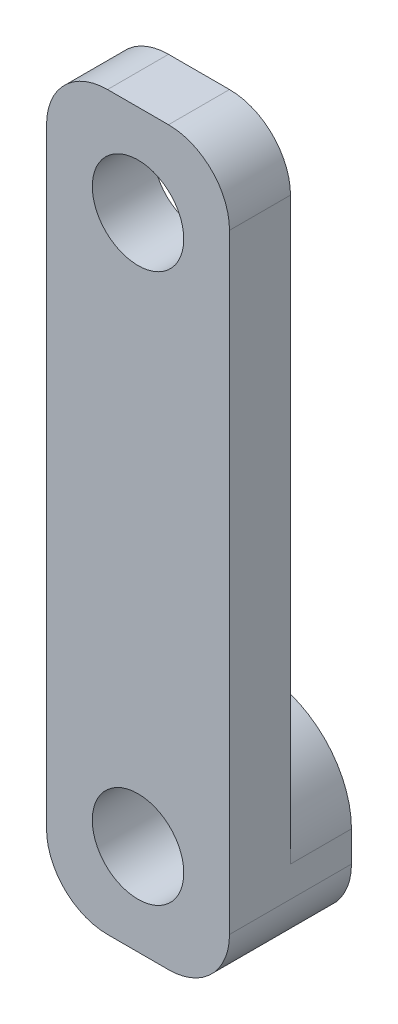
SolidWorks part; units mm, degrees
material "ABS"
ref_plane "Plan de face" through (0, 0, 0) normal (0, 0, 1) x (1, 0, 0)
ref_plane "Plan de dessus" through (0, 0, 0) normal (0, 1, 0) x (1, 0, 0)
ref_plane "Plan de droite" through (0, 0, 0) normal (1, 0, 0) x (0, 0, -1)
sketch "Esquisse2" plane through (0, 0, 0) normal (0, 0, 1) x (1, 0, 0)
  line L0 (0, 0) -> (0, 7.9658) construction
  line L1 (-3, -12) -> (3, -12)
  line L2 (-3, -12) -> (-3, 12)
  line L3 (-3, 12) -> (3, 12)
  line L4 (3, -12) -> (3, 12)
  line L5 (-3, -12) -> (3, 12) construction
  line L6 (-3, 12) -> (3, -12) construction
  circle A0 centre (0, 9) radius 1.5
  circle A1 centre (0, -9) radius 1.5
  point P0 (0, 0)
  dimension "D3" = 3
  dimension "D4" = 0
  dimension "D5" = 3
  dimension "D6" = 3
  dimension "D7" = 3
  dimension "D1" = 18
  dimension "D2" = 6
extrude "Boss.-Extru.2" add sketch "Esquisse2" along normal blind 2
fillet "Congé2" radius 2 4 edges at (-3, 12, 1) (3, 12, 1) (-3, -12, 1) (3, -12, 1)
sketch "Esquisse3" plane through (0, 0, 0) normal (0, 0, -1) x (-1, 0, 0)
  line L4 (-1, -12) -> (1, -12)
  line L5 (3, -10) -> (3, 10)
  line L6 (1, 12) -> (-1, 12)
  line L7 (-3, 10) -> (-3, -10)
  line L8 (-1, -12) -> (1, -12)
  line L9 (3, -10) -> (3, 10)
  line L10 (1, 12) -> (-1, 12)
  line L11 (-3, 10) -> (-3, -10)
  circle A0 centre (0, -9) radius 3
  circle A1 centre (0, -9) radius 1.5
  arc A7 (1, -12) -> (3, -10) centre (1, -10) ccw
  arc A8 (3, 10) -> (1, 12) centre (1, 10) ccw
  arc A9 (-1, 12) -> (-3, 10) centre (-1, 10) ccw
  arc A10 (-3, -10) -> (-1, -12) centre (-1, -10) ccw
  arc A11 (1, -12) -> (3, -10) centre (1, -10) ccw
  arc A12 (3, 10) -> (1, 12) centre (1, 10) ccw
  arc A13 (-1, 12) -> (-3, 10) centre (-1, 10) ccw
  arc A14 (-3, -10) -> (-1, -12) centre (-1, -10) ccw
  line M12 (-1, -12) -> (1, -12)
  arc M13 (1, -12) -> (3, -10) centre (1, -10) ccw
  line M14 (3, -10) -> (3, 10)
  arc M19 (-3, -10) -> (-1, -12) centre (-1, -10) ccw
  circle M20 centre (0, -9) radius 1.5
  dimension "D1" = 6
  dimension "D2" = 3
  dimension "D3" = 0
extrude "Boss.-Extru.3" add sketch "Esquisse3" along normal blind 2 contours A0 M20 | A0 L8 M13 M14 | A0 L11 M19 M12
